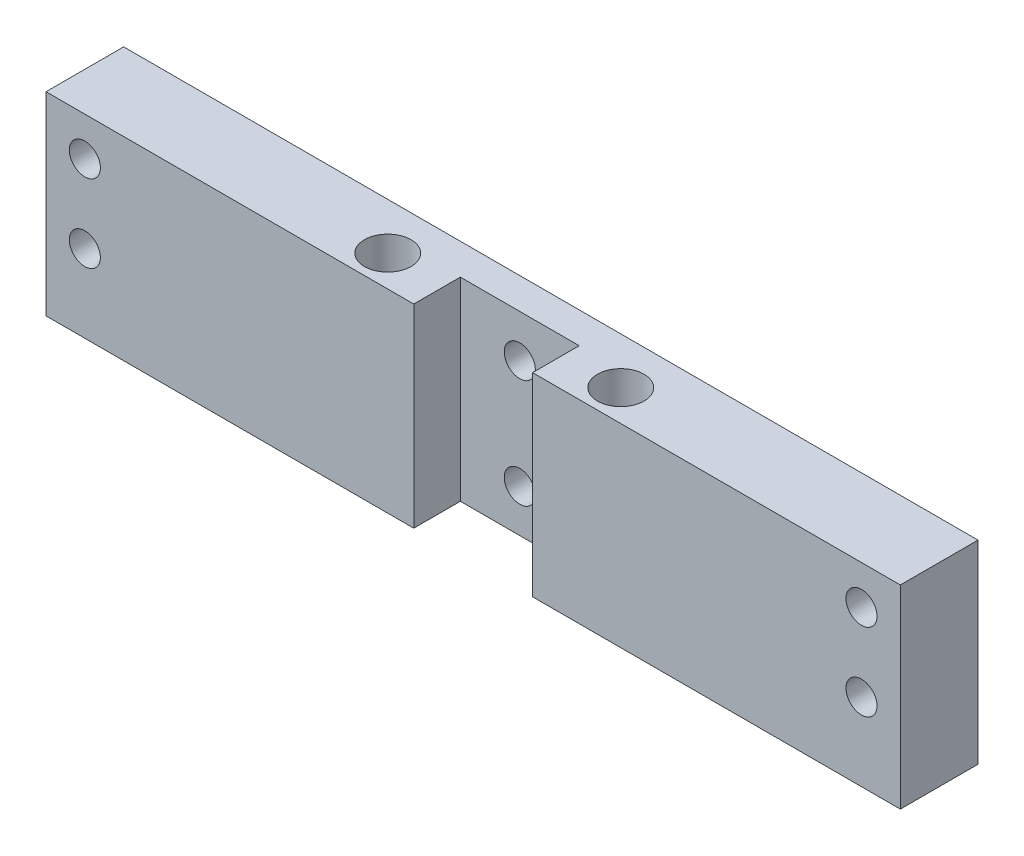
SolidWorks part; units mm, degrees
ref_plane "Plan de face" through (0, 0, 0) normal (0, 0, 1) x (1, 0, 0)
ref_plane "Plan de dessus" through (0, 0, 0) normal (0, 1, 0) x (1, 0, 0)
ref_plane "Plan de droite" through (0, 0, 0) normal (1, 0, 0) x (0, 0, -1)
sketch "Esquisse1" plane through (0, 0, 0) normal (0, 0, 1) x (1, 0, 0)
  line L0 (5, 25) -> (5, 0) construction
  line L1 (0, 0) -> (110, 0)
  line L2 (0, 0) -> (0, 25)
  line L3 (0, 25) -> (110, 25)
  line L4 (110, 0) -> (110, 25)
  line L5 (105, 0) -> (105, 25) construction
  line L6 (55, 25) -> (55, 0) construction
  circle A0 centre (5, 20) radius 2
  circle A1 centre (5, 10) radius 2
  circle A3 centre (105, 20) radius 2
  circle A4 centre (105, 10) radius 2
  circle A6 centre (55, 19.5) radius 2
  circle A7 centre (55, 5.5) radius 2
  point P29 (55, 12.5)
  dimension "D5" = 4
  dimension "D11" = 4
  dimension "D12" = 14
  dimension "D8" = 4
  dimension "D1" = 110
  dimension "D2" = 25
  dimension "D3" = 5
  dimension "D4" = 5
  dimension "D6" = 5
  dimension "D7" = 10
  dimension "D9" = 5
  dimension "D10" = 10
  dimension "D13" = 7
extrude "Boss.-Extru.1" add sketch "Esquisse1" along normal blind 10
sketch "Esquisse2" plane through (0, 0, 10) normal (0, 0, 1) x (1, 0, 0)
  line L0 (110, 25) -> (0, 25) construction
  line L1 (47.35, 25) -> (62.65, 25)
  line L2 (47.35, 25) -> (47.35, 0)
  line L3 (47.35, 0) -> (62.65, 0)
  line L4 (62.65, 25) -> (62.65, 0)
  line L5 (0, 0) -> (110, 0) construction
  line L6 (55, 25) -> (55, 0) construction
  dimension "D1" = 15.3
extrude "Enlèv. mat.-Extru.1" cut sketch "Esquisse2" against normal blind 6
sketch "Esquisse3" plane through (0, 25, 0) normal (0, 1, 0) x (1, 0, 0)
  line L0 (40, 0) -> (40, -10) construction
  line L1 (110, 0) -> (0, 0) construction
  line L2 (47.35, -10) -> (0, -10) construction
  line L3 (70, -10) -> (70, 0) construction
  line L4 (110, -10) -> (62.65, -10) construction
  line L5 (55, 0) -> (55, -4) construction
  line L6 (62.65, -4) -> (47.35, -4) construction
  circle A0 centre (70, -6) radius 3
  circle A1 centre (40, -6) radius 3
  dimension "D2" = 6
  dimension "D1" = 30
  dimension "D3" = 4
  dimension "D4" = 4
extrude "Enlèv. mat.-Extru.2" cut sketch "Esquisse3" against normal blind 15
